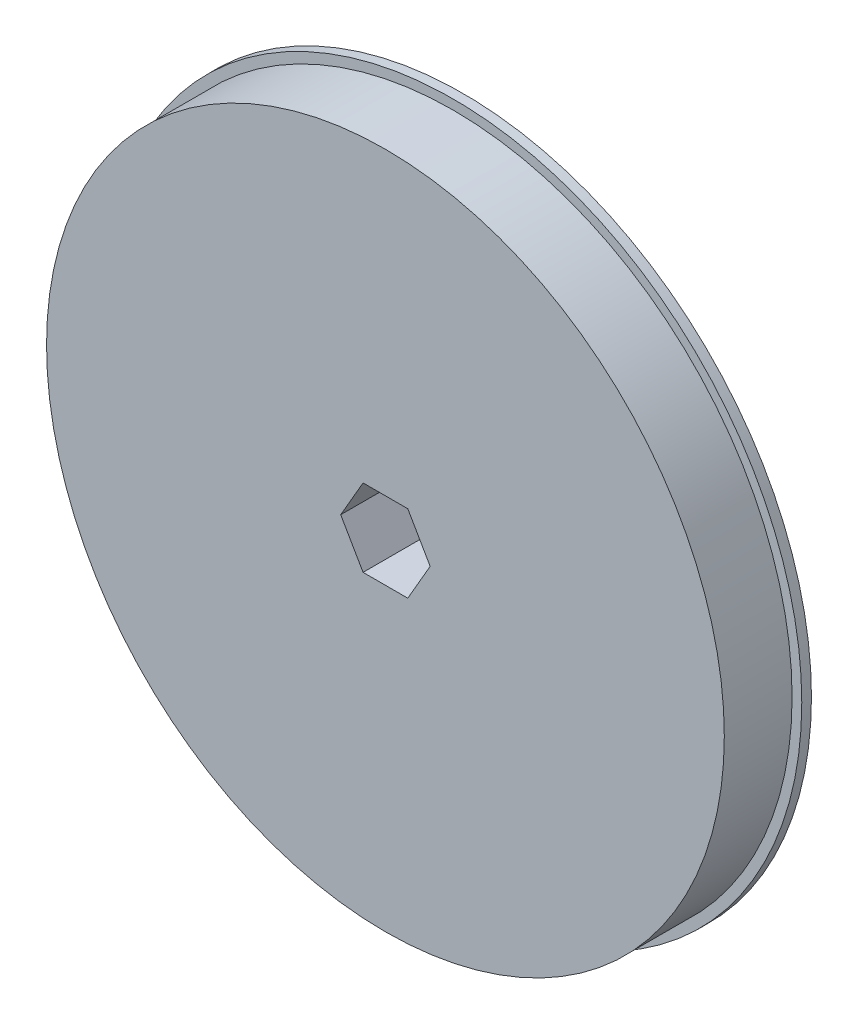
SolidWorks part; units mm, degrees
ref_plane "Front Plane" through (0, 0, 0) normal (0, 0, 1) x (1, 0, 0)
ref_plane "Top Plane" through (0, 0, 0) normal (0, 1, 0) x (1, 0, 0)
ref_plane "Right Plane" through (0, 0, 0) normal (1, 0, 0) x (0, 0, -1)
sketch "Sketch1" plane through (0, 0, 0) normal (0, 0, 1) x (1, 0, 0)
  circle A0 centre (0, 0) radius 57.15
  dimension "D1" = 114.3
extrude "Boss-Extrude1" add sketch "Sketch1" along normal blind 12.7
sketch "Sketch2" plane through (0, 0, 12.7) normal (0, 0, 1) x (1, 0, 0)
  circle A3 centre (0, 0) radius 55.5625
  circle A4 centre (0, 0) radius 57.15
  circle A5 centre (0, 0) radius 57.15
  dimension "D1" = 111.125
  dimension "D2" = 0
extrude "Cut-Extrude1" cut sketch "Sketch2" against normal blind 11.1125
sketch "Sketch3" plane through (0, 0, 0) normal (0, 0, -1) x (-1, 0, 0)
  circle A0 centre (0, 0) radius 50.8
  dimension "D1" = 101.6
extrude "Cut-Extrude2" cut sketch "Sketch3" against normal blind 9.525
sketch "Sketch4" plane through (0, 0, 9.525) normal (0, 0, -1) x (-1, 0, 0)
  circle A0 centre (0, 0) radius 12.7
  dimension "D1" = 25.4
extrude "Boss-Extrude2" add sketch "Sketch4" along normal blind 6.35
sketch "Sketch6" plane through (0, 0, 3.175) normal (0, 0, -1) x (-1, 0, 0)
  line L1 (7.3323, 0) -> (3.6662, 6.35)
  line L2 (3.6662, 6.35) -> (-3.6662, 6.35)
  line L3 (-3.6662, 6.35) -> (-7.3323, 0)
  line L4 (-7.3323, 0) -> (-3.6662, -6.35)
  line L5 (-3.6662, -6.35) -> (3.6662, -6.35)
  line L6 (3.6662, -6.35) -> (7.3323, 0)
  circle A0 centre (0, 0) radius 6.35 construction
  dimension "D1" = 12.7
extrude "Cut-Extrude4" cut sketch "Sketch6" against normal blind 12.7
chamfer "Chamfer1" distance 0.7937 angle 45 1 edges at (-12.7, 0, 3.175)
